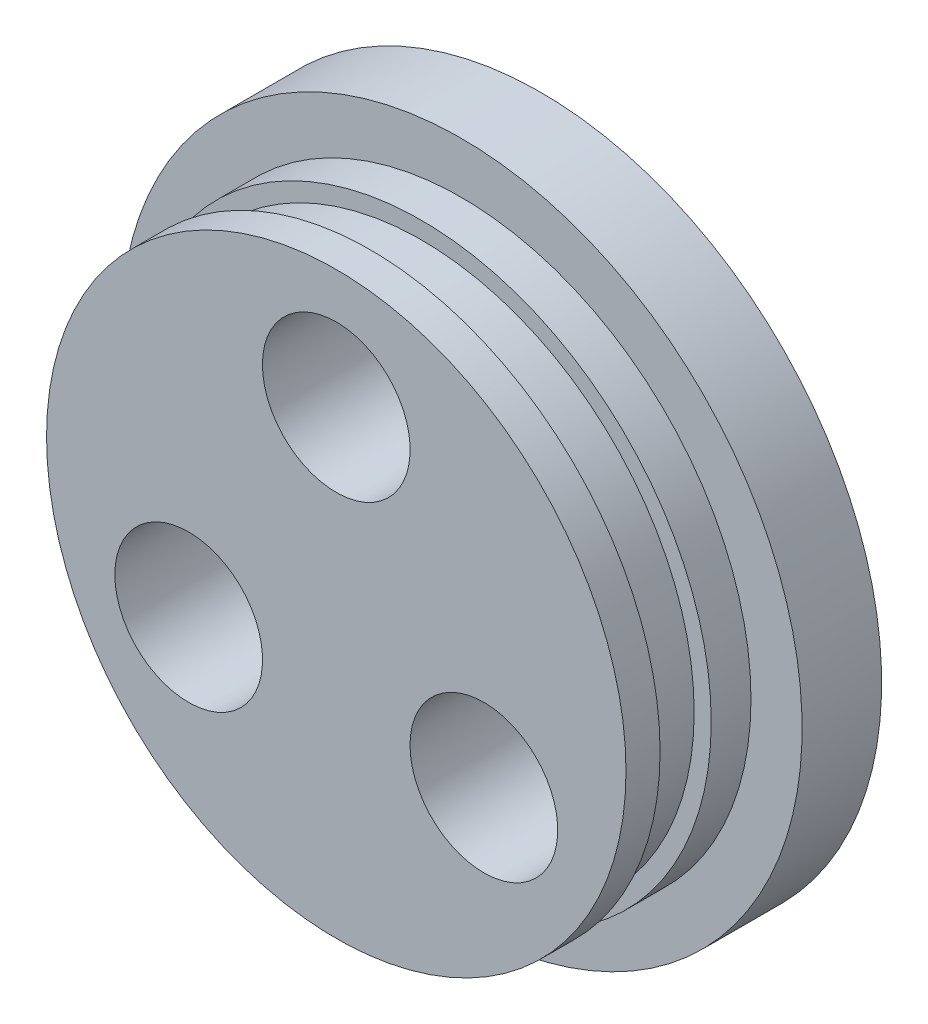
SolidWorks part; units mm, degrees
ref_plane "Front Plane" through (0, 0, 0) normal (0, 0, 1) x (1, 0, 0)
ref_plane "Top Plane" through (0, 0, 0) normal (0, 1, 0) x (1, 0, 0)
ref_plane "Right Plane" through (0, 0, 0) normal (1, 0, 0) x (0, 0, -1)
sketch "Sketch1" plane through (0, 0, 0) normal (0, 0, 1) x (1, 0, 0)
  circle A0 centre (0, 0) radius 25.5
  dimension "D1" = 51
extrude "Boss-Extrude1" add sketch "Sketch1" along normal blind 11
sketch "Sketch2" plane through (0, 0, 0) normal (0, 0, -1) x (-1, 0, 0)
  circle A0 centre (0, 0) radius 30
  dimension "D1" = 60
extrude "Boss-Extrude2" add sketch "Sketch2" along normal blind 7
ref_plane "Plane1" through (0, 0, 8) normal (0, 0, 1) x (1, 0, 0)
sketch "Sketch3" plane through (0, 0, 8) normal (0, 0, 1) x (1, 0, 0)
  circle A0 centre (0, 0) radius 24
  circle A1 centre (0, 0) radius 25.5 construction
  circle A2 centre (0, 0) radius 37.4761
  dimension "D1" = 1.5
extrude "Cut-Extrude1" cut sketch "Sketch3" against normal blind 4.5
sketch "Sketch5" plane through (0, 0, -7) normal (0, 0, -1) x (-1, 0, 0)
  line L1 (-5.6292, 11.75) -> (-12.9904, 7.5)
  line L2 (-12.9904, 7.5) -> (-12.9904, -1)
  line L6 (-7.3612, -10.75) -> (0, -15)
  line L7 (0, -15) -> (7.3612, -10.75)
  line L8 (12.9904, -1) -> (12.9904, 7.5)
  line L9 (12.9904, 7.5) -> (5.6292, 11.75)
  circle A0 centre (0, 15) radius 6.5
  circle A2 centre (-12.9904, -7.5) radius 6.5
  circle A3 centre (12.9904, -7.5) radius 6.5
  arc A4 (-5.6098, 11.7167) -> (-12.9518, -1.0001) centre (0, 0) ccw construction
  arc A5 (12.9518, -1.0001) -> (5.6098, 11.7167) centre (0, 0) ccw construction
  arc A6 (-7.342, -10.7166) -> (7.342, -10.7166) centre (0, 0) ccw construction
  point P5 (-13.5878, -7.5)
  point P12 (12.9904, -8.065)
  dimension "D1" = 13
  dimension "D3" = 13
  dimension "D4" = 13
extrude "Cut-Extrude2" cut sketch "Sketch5" against normal blind 30.5 contours A0 | A2 | A3
